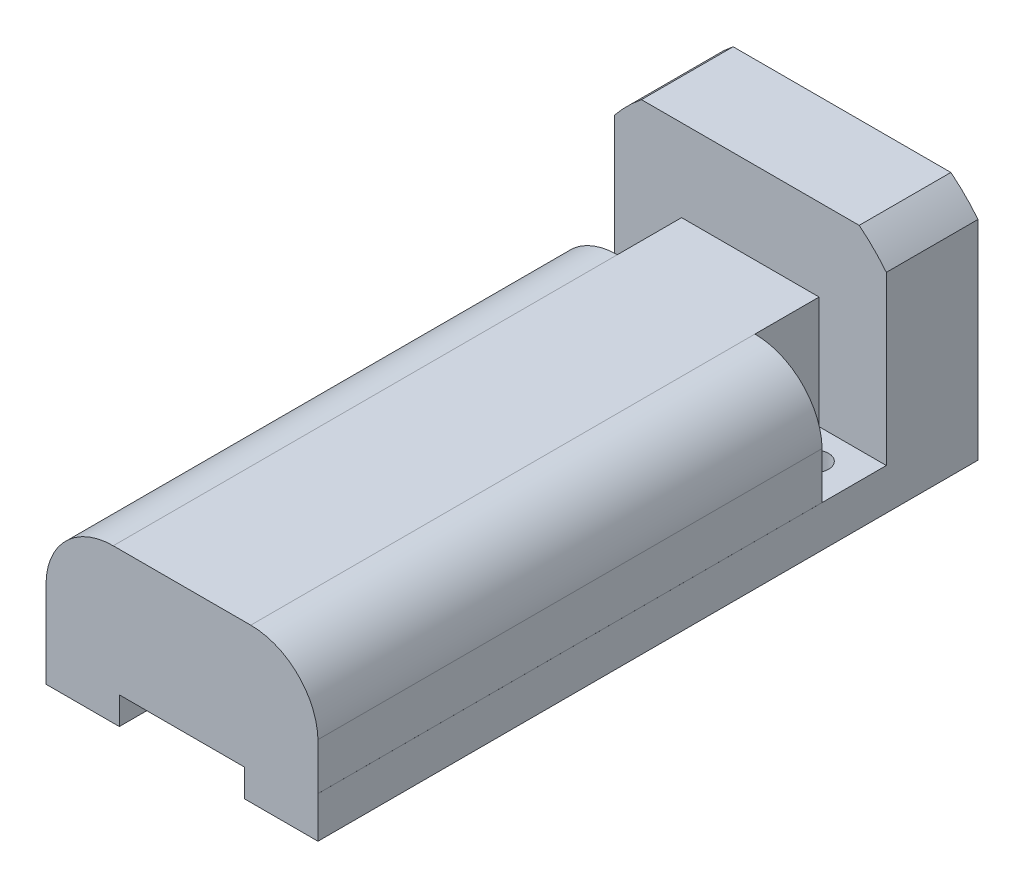
SolidWorks part; units mm, degrees
ref_plane "Front Plane" through (0, 0, 0) normal (0, 0, 1) x (1, 0, 0)
ref_plane "Top Plane" through (0, 0, 0) normal (0, 1, 0) x (1, 0, 0)
ref_plane "Right Plane" through (0, 0, 0) normal (1, 0, 0) x (0, 0, -1)
sketch "Sketch1" plane through (0, 0, 0) normal (0, 0, 1) x (1, 0, 0)
  line L0 (0, 0) -> (0, 29.3495) construction
  line L1 (-14.835, 0) -> (-6.835, 0)
  line L4 (-14.835, 0) -> (-14.835, 4.5)
  line L5 (-14.835, 4.5) -> (-8.35, 4.5)
  line L6 (14.835, 0) -> (14.835, 4.5)
  line L7 (14.835, 0) -> (6.835, 0)
  line L11 (8.35, 4.5) -> (14.835, 4.5)
  line L12 (-8.35, 4.5) -> (8.35, 4.5) construction
  line L13 (-6.835, 0) -> (6.835, 0) construction
  line L14 (-6.835, 0) -> (-6.835, 3)
  line L15 (6.835, 0) -> (6.835, 3)
  line L16 (-6.835, 3) -> (6.835, 3)
  line L17 (-8.35, 4.5) -> (8.35, 4.5)
  point P10 (0, 21.4888)
  point P13 (0, 23.4888)
  point P16 (0, 0)
  dimension "D1" = 29.67
  dimension "D2" = 8
  dimension "D3" = 3
  dimension "D4" = 4.5
extrude "Boss-Extrude1" add sketch "Sketch1" against normal blind 72 contours L15 L16 L14 L1 L4 L5 L17 L11 L6 L7
sketch "Sketch8" plane through (0, 0, -72) normal (0, 0, -1) x (-1, 0, 0)
  line L4 (-14.835, 25.7079) -> (14.835, 25.7079)
  line L8 (0, 0) -> (0, 41.6063) construction
  line L10 (-10.35, 0) -> (-10.35, 21.2229)
  line L11 (14.835, 0) -> (14.835, 25.7079)
  line L12 (10.35, 0) -> (14.835, 0)
  line L13 (-14.835, 0) -> (-10.35, 0)
  line L14 (-10.35, 21.2229) -> (10.35, 21.2229)
  line L15 (10.35, 21.2229) -> (10.35, 0)
  line L16 (-14.835, 0) -> (-6.835, 0) construction
  line L19 (-14.835, 0) -> (-14.835, 25.7079)
  arc A1 (14.8327, 22.748) -> (11.874, 25.7067) centre (0, 10.874) ccw construction
  point P26 (0, 25.7079)
  dimension "D1" = 4.485
  dimension "D2" = 4.485
  dimension "D3" = 25.7079
extrude "Boss-Extrude3" add sketch "Sketch8" against normal blind 5
sketch "Sketch9" plane through (0, 0, -72) normal (0, 0, -1) x (-1, 0, 0)
  line L0 (-15.0091, 25.8819) -> (-15.0091, 22.5275)
  line L7 (-13.437, 24.3098) -> (-15.0091, 25.8819) construction
  line L9 (-15.0091, 25.8819) -> (-11.6546, 25.8819)
  line L10 (-14.835, 25.7079) -> (14.835, 25.7079) construction
  line L11 (0, 0) -> (0, 25.7079) construction
  line L12 (15.0091, 25.8819) -> (15.0091, 22.5275)
  line L13 (15.0091, 25.8819) -> (11.6546, 25.8819)
  arc A1 (-11.6546, 25.8819) -> (-15.0091, 22.5275) centre (-0.0019, 10.8748) ccw
  arc A3 (11.6546, 25.8819) -> (15.0091, 22.5275) centre (0.0019, 10.8748) cw
  dimension "D2" = 19
  dimension "D1" = 45
  dimension "D3" = 3.3544
  dimension "D4" = 0.1741
extrude "Cut-Extrude4" cut sketch "Sketch9" against normal up to surface (5 mm away) up to face at (0, 13.9827, -67)
sketch "Sketch11" plane through (0, 0, -67) normal (0, 0, 1) x (1, 0, 0)
  line L8 (14.835, 4.5) -> (14.835, 22.7483) construction
  line L9 (11.8754, 25.7079) -> (-11.8754, 25.7079) construction
  line L10 (-14.835, 4.5) -> (-14.835, 22.7483) construction
  line L11 (14.835, 4.5) -> (14.835, 22.7483)
  line L12 (11.8754, 25.7079) -> (-11.8754, 25.7079)
  line L13 (-14.835, 4.5) -> (-14.835, 22.7483)
  line L14 (-14.835, 4.5) -> (14.835, 4.5)
  arc A4 (14.835, 22.7483) -> (11.8754, 25.7079) centre (0.0019, 10.8748) ccw construction
  arc A5 (-11.8754, 25.7079) -> (-14.835, 22.7483) centre (-0.0019, 10.8748) ccw construction
  arc A6 (14.835, 22.7483) -> (11.8754, 25.7079) centre (0.0019, 10.8748) ccw
  arc A7 (-11.8754, 25.7079) -> (-14.835, 22.7483) centre (-0.0019, 10.8748) ccw
extrude "Boss-Extrude4" add sketch "Sketch11" along normal blind 5
sketch "Sketch12" plane through (0, 0, -62) normal (0, 0, 1) x (1, 0, 0)
  line L1 (0, 0) -> (0, 30.5664) construction
  line L6 (14.8327, 0) -> (14.8327, 22.748) construction
  line L11 (7.5, 16.75) -> (-7.5, 16.75) construction
  line L12 (-14.835, 4.5) -> (14.835, 4.5)
  line L14 (-14.835, 9.415) -> (-14.835, 0) construction
  line L15 (14.8327, 4.5) -> (14.8327, 9.6002)
  line L16 (7.5, 16.75) -> (-7.5, 16.75)
  line L17 (-14.835, 9.415) -> (-14.835, 4.5)
  arc A0 (14.835, 9.415) -> (7.5, 16.75) centre (7.5, 9.415) ccw construction
  arc A1 (-7.5, 16.75) -> (-14.835, 9.415) centre (-7.5, 9.415) ccw construction
  arc A2 (14.8327, 9.6002) -> (7.5, 16.75) centre (7.5, 9.415) ccw
  arc A3 (-7.5, 16.75) -> (-14.835, 9.415) centre (-7.5, 9.415) ccw
  point P8 (0, 4.5)
  point P13 (0, 11.75)
  point P23 (0, 16.75)
extrude "Boss-Extrude5" add sketch "Sketch12" along normal up to surface (55 mm away) from offset 7 up to face at (0, 1.875, 0)
sketch "Sketch18" plane through (0, 0, -72) normal (0, 0, -1) x (-1, 0, 0)
  line L0 (6.835, 0) -> (6.835, 3) construction
  line L2 (-10.35, 4.5) -> (-10.35, 0)
  line L3 (-10.35, 0) -> (-6.835, 0)
  line L5 (10.35, 4.5) -> (-10.35, 4.5)
  line L6 (10.35, 4.5) -> (10.35, 0)
  line L7 (10.35, 0) -> (6.835, 0)
  line L9 (-6.835, 0) -> (-6.835, 3) construction
  line L10 (6.835, 3) -> (-6.835, 3) construction
  line L11 (6.835, 0) -> (6.835, 3)
  line L12 (-6.835, 0) -> (-6.835, 3)
  line L13 (6.835, 3) -> (-6.835, 3)
extrude "Cut-Extrude8" cut sketch "Sketch18" against normal up to surface (5 mm away) up to face at (0, 12.8614, -67)
sketch "Sketch19" plane through (0, 0, -55) normal (0, 0, -1) x (-1, 0, 0)
  line L0 (14.835, 4.5) -> (-14.8327, 4.5) construction
  line L1 (-7.5, 16.75) -> (7.5, 16.75)
  line L2 (-7.5, 16.75) -> (-7.5, 4.5)
  line L3 (-7.5, 4.5) -> (7.5, 4.5)
  line L4 (7.5, 16.75) -> (7.5, 4.5)
  arc A0 (-7.5, 16.75) -> (-14.8327, 9.6002) centre (-7.5, 9.415) ccw construction
  arc A1 (14.835, 9.415) -> (7.5, 16.75) centre (7.5, 9.415) ccw construction
extrude "Boss-Extrude8" add sketch "Sketch19" along normal up to surface (7 mm away) up to face at (0, 17.6793, -62)
sketch "Sketch20" plane through (0, 4.5, 0) normal (0, 1, 0) x (1, 0, 0)
  line L0 (-14.835, 58.5) -> (-7.5, 58.5) construction
  line L1 (-14.835, 62) -> (-14.835, 55) construction
  line L2 (-7.5, 62) -> (-7.5, 55) construction
  line L3 (-10.5425, 62) -> (-10.5425, 55) construction
  line L6 (0, 62) -> (0, 0) construction
  line L7 (11.8754, 62) -> (-11.8754, 62) construction
  circle A0 centre (-10.5425, 58.5) radius 1.5
  circle A1 centre (10.5425, 58.5) radius 1.5
  dimension "D1" = 3
  dimension "D2" = 4.2925
extrude "Cut-Extrude9" cut sketch "Sketch20" against normal up to next
sketch "Sketch21" plane through (0, 0, -72) normal (0, 0, -1) x (-1, 0, 0)
  line L6 (-11.85, 0) -> (11.85, 0)
  line L9 (11.85, 22.7229) -> (11.85, 0)
  line L10 (-11.85, 22.7229) -> (11.85, 22.7229)
  line L11 (-11.85, 0) -> (-11.85, 22.7229)
  line L12 (11.85, 22.7229) -> (11.85, 0)
  line L13 (-11.85, 22.7229) -> (11.85, 22.7229)
  line L14 (-11.85, 0) -> (-11.85, 22.7229)
  dimension "D1" = 1.5
extrude "Cut-Extrude10" cut sketch "Sketch21" against normal blind 7
